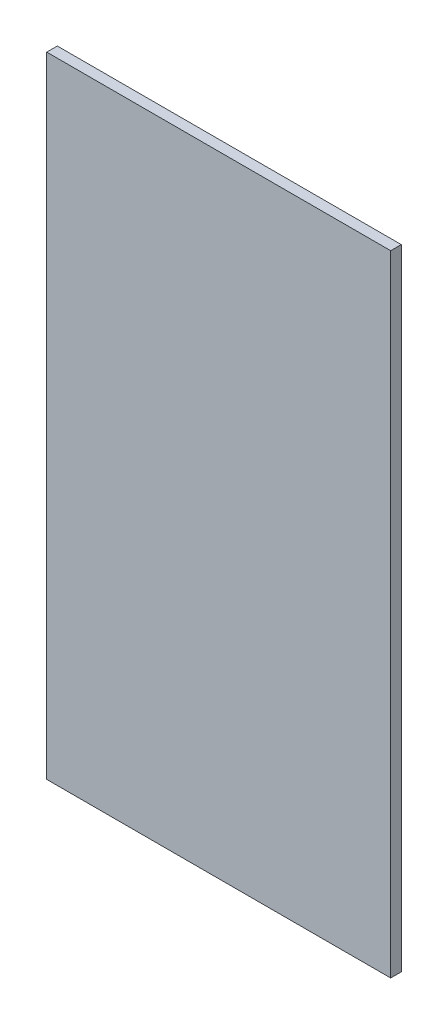
SolidWorks part; units mm, degrees
ref_plane "Plan de face" through (0, 0, 0) normal (0, 0, 1) x (1, 0, 0)
ref_plane "Plan de dessus" through (0, 0, 0) normal (0, 1, 0) x (1, 0, 0)
ref_plane "Plan de droite" through (0, 0, 0) normal (1, 0, 0) x (0, 0, -1)
sketch "Esquisse1" plane through (0, 0, 0) normal (0, 0, 1) x (1, 0, 0)
  line L1 (-82.1418, 217.7685) -> (80.3582, 217.7685)
  line L2 (-82.1418, 217.7685) -> (-82.1418, -79.8315)
  line L3 (-82.1418, -79.8315) -> (80.3582, -79.8315)
  line L4 (80.3582, 217.7685) -> (80.3582, -79.8315)
extrude "Boss.-Extru.2" add sketch "Esquisse1" along normal blind 5 contours L2 L1 L4 L3
sketch3d "Esquisse3D1" [suppressed]
  line L0 (25.4949, 138.1354, 0) -> (24.8506, 141.2765, 0)
  line L1 (24.8506, 141.2765, 0) -> (26.703, 140.5516, 0)
  line L2 (26.703, 140.5516, 0) -> (25.7982, 142.6197, 0)
  line L3 (25.7982, 142.6197, 0) -> (27.3876, 142.404, 0)
  line L4 (33.6186, 143.1405, 0) -> (35.1655, 140.581, 0)
  line L5 (35.1655, 140.581, 0) -> (32.9355, 140.9303, 0)
  line L6 (32.9355, 140.9303, 0) -> (34.252, 139.5332, 0)
  line L7 (34.252, 139.5332, 0) -> (32.64, 138.781, 0)
  line L8 (32.64, 138.781, 0) -> (34.252, 136.8197, 0)
  line L9 (34.252, 136.8197, 0) -> (31.3863, 137.0998, 0)
  line L10 (31.3863, 137.0998, 0) -> (31.3863, 135.0465, 0)
  line L11 (-7.8933, 102.1902, 0) -> (-6.8333, 103.7111, 0)
  line L12 (-6.8333, 103.7111, 0) -> (-4.8975, 102.1902, 0)
  line L13 (44.4221, 93.8184, 0) -> (52.0224, 96.6312, 0)
  line L14 (52.0224, 96.6312, 0) -> (51.3025, 98.5764, 0)
  line L15 (51.3025, 98.5764, 0) -> (44.2109, 95.6765, 0)
  line L16 (47.6223, 90.9727, 0) -> (53.8358, 90.9727, 0)
  line L17 (53.8358, 90.9727, 0) -> (54.506, 89.3336, 0)
  line L18 (54.506, 89.3336, 0) -> (48.2236, 89.0886, 0)
  line L19 (43.8542, 83.717, 0) -> (43.8542, 85.5209, 0)
  line L20 (-40.7515, 93.6509, 0) -> (-50.4113, 95.8339, 0)
  line L21 (-50.4113, 95.8339, 0) -> (-50.7933, 97.5258, 0)
  line L22 (-50.7933, 97.5258, 0) -> (-40.296, 95.1535, 0)
  line L23 (-55.0501, 88.248, 0) -> (-45.1721, 89.5578, 0)
  line L24 (-45.4449, 91.1951, 0) -> (-55.323, 89.8853, 0)
  line L25 (-59.5014, 81.3608, 0) -> (-38.9454, 86.0024, 0)
  line L26 (-38.9454, 86.0024, 0) -> (-39.4037, 88.032, 0)
  line L27 (-39.4037, 88.032, 0) -> (-59.3142, 83.0458, 0)
  line L28 (-59.3142, 83.0458, 0) -> (-59.5014, 81.3608, 0)
  line L29 (-19.8014, 144.3855, 0) -> (-17.5483, 143.5845, 0)
  line L30 (-17.5483, 143.5845, 0) -> (-18.7753, 143.3169, 0)
  line L31 (-18.7753, 143.3169, 0) -> (-16.7171, 142.5851, 0)
  line L32 (-16.7171, 142.5851, 0) -> (-18.7374, 141.44, 0)
  line L33 (-18.7374, 141.44, 0) -> (-18.7374, 140.4351, 0)
  line L34 (-25.2305, 145.307, 0) -> (-27.1997, 143.6168, 0)
  line L35 (-27.1997, 143.6168, 0) -> (-25.2563, 142.8175, 0)
  line L36 (-25.2563, 142.8175, 0) -> (-26.8236, 140.7957, 0)
  line L37 (-26.8236, 140.7957, 0) -> (-25.554, 139.9964, 0)
  line L38 (-25.554, 139.9964, 0) -> (-26.5605, 138.6981, 0)
  line L39 (-26.5605, 138.6981, 0) -> (-24.4569, 139.1657, 0)
  line L40 (-24.4569, 139.1657, 0) -> (-24.5171, 138.2709, 0)
  line L41 (-13.6094, 141.3107, 0) -> (-13.6094, 141.8817, 0)
  line L42 (-13.6094, 141.8817, 0) -> (-14.3403, 142.6127, 0)
  line L43 (-14.3403, 142.6127, 0) -> (-13.4864, 142.6127, 0)
  line L44 (-13.4864, 142.6127, 0) -> (-14.1883, 143.5119, 0)
  line L45 (-14.1883, 143.5119, 0) -> (-14.1172, 144.0887, 0)
  line L46 (-14.1172, 144.0887, 0) -> (-12.8524, 143.7836, 0)
  line L47 (-12.8524, 143.7836, 0) -> (-12.5954, 145.8685, 0)
  line L48 (-12.5954, 145.8685, 0) -> (-11.6249, 144.898, 0)
  line L49 (-11.6249, 144.898, 0) -> (-11.6249, 145.9572, 0)
  line L50 (-11.6249, 145.9572, 0) -> (-10.7216, 145.054, 0)
  line L51 (-10.7216, 145.054, 0) -> (-10.2033, 146.2516, 0)
  line L52 (-10.2033, 146.2516, 0) -> (-9.592, 146.2516, 0)
  line L53 (-9.592, 146.2516, 0) -> (-9.592, 144.8252, 0)
  line L54 (-9.592, 144.8252, 0) -> (-8.3693, 144.8252, 0)
  line L55 (-8.3693, 144.8252, 0) -> (-8.8222, 144.3723, 0)
  line L56 (-8.8222, 144.3723, 0) -> (-8.1316, 143.6817, 0)
  line L57 (-8.1316, 143.6817, 0) -> (-9.0308, 142.786, 0)
  circle A0 centre (20.6935, 109.8595, 0) radius 0.7549
  circle A1 centre (-18.212, 111.9103, 0) radius 1.2299
  spline S0 degree 2 poles (-20.3633, 162.7652, 0) (-12.0724, 165.7872, 0) (-3.3622, 164.1853, 0) knots 0 0 0 1 1 1
  spline S1 degree 2 poles (-81.8789, 154.9416, 0) (-71.547, 187.9168, 0) (-40.4422, 200.8183, 0) knots 0 0 0 1 1 1
  spline S2 degree 2 poles (-30.1118, 204.7729, 0) (-22.0747, 208.713, 0) (-13.1407, 209.3049, 0) knots 0 0 0 1 1 1
  spline S3 degree 2 poles (-30.1118, 204.7729, 0) (-23.7254, 212.8374, 0) (-13.6228, 210.7513, 0) knots 0 0 0 1 1 1
  spline S4 degree 1 poles (-38.3081, 201.6872, 0) (-33.101, 203.905, 0) knots 0 0 1 1
  spline S5 degree 2 poles (-38.3081, 201.6872, 0) (-32.1102, 216.2852, 0) (-16.612, 212.2942, 0) knots 0 0 0 1 1 1
  spline S6 degree 2 poles (-33.101, 203.905, 0) (-27.269, 212.5853, 0) (-16.612, 212.2942, 0) knots 0 0 0 1 1 1
  spline S7 degree 2 poles (-40.4422, 200.8183, 0) (-33.2225, 220.256, 0) (-13.5264, 212.3906, 0) knots 0 0 0 1 1 1
  spline S8 degree 2 poles (-74.1656, 164.0776, 0) (-63.2097, 185.081, 0) (-42.1866, 195.7719, 0) knots 0 0 0 1 1 1
  spline S9 degree 2 poles (-74.1656, 164.0776, 0) (-68.3516, 165.8152, 0) (-62.304, 166.0704, 0) knots 0 0 0 1 1 1
  spline S10 degree 2 poles (-62.304, 166.0704, 0) (-57.137, 181.3077, 0) (-43.0407, 188.655, 0) knots 0 0 0 1 1 1
  spline S11 degree 2 poles (-43.0407, 188.655, 0) (-42.6351, 192.216, 0) (-42.1866, 195.7719, 0) knots 0 0 0 1 1 1
  spline S12 degree 2 poles (-42.1039, 189.1121, 0) (-39.3919, 191.2502, 0) (-36.4025, 192.9733, 0) knots 0 0 0 1 1 1
  spline S13 degree 2 poles (-42.1039, 189.1121, 0) (-41.8681, 192.8762, 0) (-40.4146, 196.3519, 0) knots 0 0 0 1 1 1
  spline S14 degree 2 poles (-40.4146, 196.3519, 0) (-37.3779, 198.6245, 0) (-34.0194, 200.3942, 0) knots 0 0 0 1 1 1
  spline S15 degree 2 poles (-36.4025, 192.9733, 0) (-35.4533, 196.7619, 0) (-34.0194, 200.3942, 0) knots 0 0 0 1 1 1
  spline S16 degree 2 poles (-28.6197, 202.7471, 0) (-30.5389, 199.6184, 0) (-32.2698, 196.3821, 0) knots 0 0 0 1 1 1
  spline S17 degree 2 poles (-32.2698, 196.3821, 0) (-33.9733, 195.2148, 0) (-35.3467, 193.6672, 0) knots 0 0 0 1 1 1
  spline S18 degree 2 poles (-35.3467, 193.6672, 0) (-34.5925, 197.836, 0) (-32.2698, 201.3595, 0) knots 0 0 0 1 1 1
  spline S19 degree 2 poles (-32.2698, 201.3595, 0) (-30.5285, 202.2743, 0) (-28.6197, 202.7471, 0) knots 0 0 0 1 1 1
  spline S20 degree 2 poles (-60.4696, 166.1594, 0) (-54.2515, 166.3089, 0) (-48.1266, 165.2464, 0) knots 0 0 0 1 1 1
  spline S21 degree 2 poles (-60.4696, 166.1594, 0) (-55.4726, 179.4779, 0) (-43.3205, 186.6548, 0) knots 0 0 0 1 1 1
  spline S22 degree 2 poles (-43.3205, 186.6548, 0) (-42.3946, 175.2561, 0) (-48.1266, 165.2464, 0) knots 0 0 0 1 1 1
  spline S23 degree 2 poles (-41.7618, 187.1744, 0) (-41.2309, 175.3441, 0) (-46.8276, 164.8978, 0) knots 0 0 0 1 1 1
  spline S24 degree 2 poles (-46.8276, 164.8978, 0) (-43.247, 163.3476, 0) (-39.4887, 162.3, 0) knots 0 0 0 1 1 1
  spline S25 degree 1 poles (-41.7618, 187.1744, 0) (-36.5661, 191.3959, 0) knots 0 0 1 1
  spline S26 degree 2 poles (-36.5661, 191.3959, 0) (-40.8864, 177.7324, 0) (-37.4753, 163.8587, 0) knots 0 0 0 1 1 1
  spline S27 degree 1 poles (-39.4887, 162.3, 0) (-37.4753, 163.8587, 0) knots 0 0 1 1
  spline S28 degree 2 poles (-76.2798, 159.5792, 0) (-69.992, 162.7295, 0) (-62.9649, 162.8139, 0) knots 0 0 0 1 1 1
  spline S29 degree 2 poles (-76.2798, 159.5792, 0) (-69.9421, 161.1878, 0) (-63.4163, 161.3345, 0) knots 0 0 0 1 1 1
  spline S30 degree 1 poles (-63.4163, 161.3345, 0) (-62.9649, 162.8139, 0) knots 0 0 1 1
  spline S31 degree 2 poles (-61.3909, 162.9674, 0) (-55.0995, 163.4742, 0) (-49.0038, 161.9057, 0) knots 0 0 0 1 1 1
  spline S32 degree 2 poles (-61.7094, 161.5517, 0) (-55.5657, 162.2035, 0) (-49.5347, 160.9147, 0) knots 0 0 0 1 1 1
  spline S33 degree 1 poles (-61.7094, 161.5517, 0) (-61.3909, 162.9674, 0) knots 0 0 1 1
  spline S34 degree 1 poles (-49.5347, 160.9147, 0) (-49.0038, 161.9057, 0) knots 0 0 1 1
  spline S35 degree 2 poles (-48.0169, 161.6806, 0) (-43.5, 161.5556, 0) (-39.4656, 159.5212, 0) knots 0 0 0 1 1 1
  spline S36 degree 1 poles (-48.5064, 160.5577, 0) (-48.0169, 161.6806, 0) knots 0 0 1 1
  spline S37 degree 2 poles (-48.5064, 160.5577, 0) (-43.7468, 159.7781, 0) (-39.3793, 157.7361, 0) knots 0 0 0 1 1 1
  spline S38 degree 2 poles (-39.4656, 159.5212, 0) (-22.4346, 170.5781, 0) (-2.079, 169.8481, 0) knots 0 0 0 1 1 1
  spline S39 degree 2 poles (-39.3793, 157.7361, 0) (-22.481, 169.1841, 0) (-2.1495, 167.9444, 0) knots 0 0 0 1 1 1
  spline S40 degree 2 poles (-2.079, 169.8481, 0) (7.837, 174.0448, 0) (18.3102, 176.5544, 0) knots 0 0 0 1 1 1
  spline S41 degree 2 poles (-2.1495, 167.9444, 0) (7.3531, 172.8749, 0) (17.9103, 174.612, 0) knots 0 0 0 1 1 1
  spline S42 degree 1 poles (17.9103, 174.612, 0) (18.3102, 176.5544, 0) knots 0 0 1 1
  spline S43 degree 2 poles (19.429, 174.7579, 0) (30.2167, 177.6524, 0) (40.0743, 172.5823, 0) knots 0 0 0 1 1 1
  spline S44 degree 1 poles (19.429, 174.7579, 0) (19.5216, 176.6095, 0) knots 0 0 1 1
  spline S45 degree 2 poles (19.5216, 176.6095, 0) (24.9252, 177.4093, 0) (30.3534, 176.8409, 0) knots 0 0 0 1 1 1
  spline S46 degree 2 poles (34.8635, 176.1715, 0) (36.5707, 175.4775, 0) (38.3125, 174.8754, 0) knots 0 0 0 1 1 1
  spline S47 degree 2 poles (40.0743, 172.5823, 0) (54.0193, 182.7239, 0) (71.236, 182.351, 0) knots 0 0 0 1 1 1
  spline S48 degree 3 poles (38.3125, 174.8754, 0) (49.367, 179.5773, 0) (58.4974, 187.4411, 0) (71.236, 182.351, 0) knots 0 0 0 0 1 1 1 1
  spline S49 degree 2 poles (-0.3107, 166.5454, 5) (8.2133, 168.9997, 5) (17.0379, 169.8968, 5) knots 0 0 0 1 1 1
  spline S50 degree 2 poles (18.2651, 169.4734, 0) (28.9991, 169.6026, 0) (39.2311, 166.3451, 0) knots 0 0 0 1 1 1
  spline S51 degree 2 poles (-0.3107, 166.5454, 5) (0.2947, 156.6212, 5) (2.3737, 146.8992, 5) knots 0 0 0 1 1 1
  spline S52 degree 2 poles (-3.3622, 164.1853, 0) (-1.3802, 155.3146, 0) (-1.0378, 146.2353, 0) knots 0 0 0 1 1 1
  spline S53 degree 2 poles (2.3737, 146.8992, 5) (5.1648, 147.1501, 5) (7.9657, 147.0707, 5) knots 0 0 0 1 1 1
  spline S54 degree 2 poles (7.9657, 147.0707, 5) (5.7987, 145.3956, 5) (3.5567, 143.822, 5) knots 0 0 0 1 1 1
  spline S55 degree 2 poles (-26.4609, 203.3989, 0) (-29.8737, 196.9084, 0) (-35.432, 192.118, 0) knots 0 0 0 1 1 1
  spline S56 degree 3 poles (-35.432, 192.118, 0) (-37.2126, 186.143, 0) (-37.7046, 177.1886, 0) (-37.8705, 168.5072, 0) (-35.9602, 164.8776, 0) knots 0 0 0 0 0.597354 1 1 1 1
  spline S57 degree 2 poles (-26.4609, 203.3989, 0) (-18.3206, 205.6479, 0) (-9.9003, 206.3588, 0) knots 0 0 0 1 1 1
  spline S58 degree 2 poles (-6.9753, 185.3091, 0) (-5.6223, 196.2378, 0) (-9.9003, 206.3588, 0) knots 0 0 0 1 1 1
  spline S59 degree 2 poles (-5.6694, 185.9881, 0) (-2.2964, 196.9777, 0) (-8.3855, 206.62, 0) knots 0 0 0 1 1 1
  spline S60 degree 2 poles (-8.3855, 206.62, 0) (-2.3112, 207.5622, 0) (3.8369, 207.508, 0) knots 0 0 0 1 1 1
  spline S61 degree 2 poles (-5.6694, 185.9881, 0) (-0.7771, 188.0567, 0) (4.307, 189.5921, 0) knots 0 0 0 1 1 1
  spline S62 degree 2 poles (3.8369, 207.508, 0) (3.1718, 198.5253, 0) (4.307, 189.5921, 0) knots 0 0 0 1 1 1
  spline S63 degree 2 poles (5.3216, 190.0513, 0) (16.4175, 194.2656, 0) (24.3421, 203.1003, 0) knots 0 0 0 1 1 1
  spline S64 degree 2 poles (5.3216, 190.0513, 0) (4.0876, 198.7199, 0) (4.8055, 207.4499, 0) knots 0 0 0 1 1 1
  spline S65 degree 2 poles (4.8055, 207.4499, 0) (14.9501, 206.9868, 0) (24.3421, 203.1003, 0) knots 0 0 0 1 1 1
  spline S66 degree 2 poles (-13.5264, 212.3906, 0) (-12.8637, 213.8075, 0) (-11.7744, 214.9114, 0) knots 0 0 0 1 1 1
  spline S67 degree 2 poles (-11.7744, 214.9114, 0) (-11.8968, 216.2353, 0) (-12.829, 217.1908, 0) knots 0 0 0 1 1 1
  spline S68 degree 2 poles (-12.829, 217.1908, 0) (-12.397, 217.5679, 0) (-11.8278, 217.5417, 0) knots 0 0 0 1 1 1
  spline S69 degree 2 poles (-11.8278, 217.5417, 0) (-11.4021, 216.4098, 0) (-10.8601, 215.3284, 0) knots 0 0 0 1 1 1
  spline S70 degree 2 poles (-10.8601, 215.3284, 0) (-9.6033, 215.1745, 0) (-8.4338, 215.6233, 0) knots 0 0 0 1 1 1
  spline S71 degree 2 poles (-8.4338, 215.6233, 0) (-6.9374, 213.4569, 0) (-8.054, 211.0468, 0) knots 0 0 0 1 1 1
  spline S72 degree 1 poles (-8.054, 211.0468, 0) (-6.9336, 211.0468, 0) knots 0 0 1 1
  spline S73 degree 2 poles (-6.9336, 211.0468, 0) (-6.4376, 213.3987, 0) (-4.5599, 214.8068, 0) knots 0 0 0 1 1 1
  spline S74 degree 1 poles (-4.5599, 214.8068, 0) (-3.6674, 214.8068, 0) knots 0 0 1 1
  spline S75 degree 2 poles (-3.6674, 214.8068, 0) (-2.5044, 215.4736, 0) (-1.7304, 216.5728, 0) knots 0 0 0 1 1 1
  spline S76 degree 1 poles (-1.7304, 216.5728, 0) (-0.7619, 215.7752, 0) knots 0 0 1 1
  spline S77 degree 2 poles (-0.7619, 215.7752, 0) (-1.8056, 215.0951, 0) (-2.8318, 214.389, 0) knots 0 0 0 1 1 1
  spline S78 degree 2 poles (-2.8318, 214.389, 0) (-2.304, 213.5052, 0) (-2.2621, 212.471, 0) knots 0 0 0 1 1 1
  spline S79 degree 3 poles (-2.2621, 212.471, 0) (-0.8127, 215.1566, 0) (4.5483, 215.9031, 0) (4.7186, 211.3255, 0) knots 0 0 0 0 1 1 1 1
  spline S80 degree 1 poles (-1.2795, 211.1904, 0) (3.4488, 211.1634, 0) knots 0 0 1 1
  spline S81 degree 2 poles (-1.2795, 211.1904, 0) (-0.8983, 213.4433, 0) (1.4494, 213.487, 0) knots 0 0 0 1 1 1
  spline S82 degree 1 poles (3.4488, 211.1634, 0) (3.4488, 211.8929, 0) knots 0 0 1 1
  spline S83 degree 2 poles (3.4488, 211.8929, 0) (2.6866, 212.721, 0) (1.5575, 212.8926, 0) knots 0 0 0 1 1 1
  spline S84 degree 1 poles (1.5575, 212.8926, 0) (1.4494, 213.487, 0) knots 0 0 1 1
  spline S85 degree 2 poles (4.7186, 211.3255, 0) (10.3448, 210.842, 0) (15.8791, 209.7244, 0) knots 0 0 0 1 1 1
  spline S86 degree 3 poles (15.8791, 209.7244, 0) (25.0713, 214.7973, 0) (32.7248, 215.4471, 0) (37.3752, 204.8654, 0) knots 0 0 0 0 1 1 1 1
  spline S87 degree 2 poles (18.5993, 209.2881, 0) (27.1258, 207.7311, 0) (35.403, 205.1641, 0) knots 0 0 0 1 1 1
  spline S88 degree 2 poles (18.5993, 209.2881, 0) (29.2578, 216.5573, 0) (35.403, 205.1641, 0) knots 0 0 0 1 1 1
  spline S89 degree 2 poles (30.7317, 202.5764, 0) (39.609, 193.2632, 0) (40.7346, 180.3478, 0) knots 0 0 0 1 1 1
  spline S90 degree 2 poles (30.7317, 202.5764, 0) (43.615, 195.0713, 0) (40.7346, 180.3478, 0) knots 0 0 0 1 1 1
  spline S91 degree 2 poles (37.3752, 204.8654, 0) (61.4632, 197.8726, 0) (80.1441, 181.1197, 0) knots 0 0 0 1 1 1
  spline S92 degree 2 poles (80.1441, 181.1197, 0) (71.9955, 179.743, 0) (64.2587, 176.8256, 0) knots 0 0 0 1 1 1
  spline S93 degree 2 poles (-20.3633, 162.7652, 0) (-18.4917, 155.1787, 0) (-17.5626, 147.4248, 0) knots 0 0 0 1 1 1
  spline S94 degree 3 poles (-25.3765, 160.8618, 0) (-25.8876, 157.4446, 0) (-29.3098, 150.9494, 0) (-27.497, 146.32, 0) (-25.2305, 145.307, 0) knots 0 0 0 0 0.669542 1 1 1 1
  spline S95 degree 2 poles (-13.6558, 181.193, 0) (-20.0535, 177.8034, 0) (-25.3006, 172.8088, 0) knots 0 0 0 1 1 1
  spline S96 degree 3 poles (39.2311, 166.3451, 0) (37.3085, 163.6675, 0) (35.5849, 160.7515, 0) (31.7572, 155.5609, 0) (29.6845, 153.1021, 0) (28.466, 150.3725, 0) (30.219, 147.5099, 0) (29.9717, 146.1817, 0) (29.0598, 144.7175, 0) knots 0 0 0 0 0.365812 0.436766 0.679225 0.725166 0.865872 1 1 1 1
  spline S97 degree 2 poles (17.0379, 169.8968, 5) (17.8049, 159.8318, 5) (15.2967, 150.0591, 5) knots 0 0 0 1 1 1
  spline S98 degree 2 poles (18.2651, 169.4734, 0) (18.642, 159.407, 0) (16.0406, 149.6871, 0) knots 0 0 0 1 1 1
  spline S99 degree 2 poles (25.4949, 138.1354, 0) (19.8938, 140.938, 0) (13.8167, 142.4443, 0) knots 0 0 0 1 1 1
  spline S100 degree 1 poles (29.0598, 144.7175, 0) (25.8573, 145.2632, 0) knots 0 0 1 1
  spline S101 degree 1 poles (25.8573, 145.2632, 0) (27.3876, 142.404, 0) knots 0 0 1 1
  spline S102 degree 2 poles (62.7677, 176.1123, 0) (51.1108, 172.8074, 0) (41.2557, 165.7526, 0) knots 0 0 0 1 1 1
  spline S103 degree 2 poles (-25.3765, 160.8618, 0) (-34.8575, 158.6597, 0) (-41.7887, 151.8381, 0) knots 0 0 0 1 1 1
  spline S104 degree 2 poles (-41.7887, 151.8381, 0) (-45.5723, 154.0646, 0) (-49.6475, 155.694, 0) knots 0 0 0 1 1 1
  spline S105 degree 3 poles (-49.6475, 155.694, 0) (-50.3292, 152.7209, 0) (-51.263, 147.5915, 0) (-48.4379, 141.0974, 0) (-49.9537, 137.6286, 0) knots 0 0 0 0 0.406946 1 1 1 1
  spline S106 degree 3 poles (-49.9537, 137.6286, 0) (-49.4637, 141.7607, 0) (-51.9256, 146.6221, 0) (-51.0045, 152.9563, 0) (-50.3667, 156.0071, 0) knots 0 0 0 0 0.604226 1 1 1 1
  spline S107 degree 2 poles (-50.3667, 156.0071, 0) (-55.8567, 159.1908, 0) (-62.2451, 158.7047, 0) knots 0 0 0 1 1 1
  spline S108 degree 2 poles (-81.8789, 154.9416, 0) (-73.1076, 158.718, 0) (-63.52, 158.8017, 0) knots 0 0 0 1 1 1
  spline S109 degree 1 poles (-35.9602, 164.8776, 0) (-34.1549, 166.0675, 0) knots 0 0 1 1
  spline S110 degree 1 poles (19.475, 178.4365, 0) (20.6201, 178.551, 0) knots 0 0 1 1
  spline S111 degree 2 poles (19.475, 178.4365, 0) (20.2478, 181.8847, 0) (21.9943, 184.9637, 0) knots 0 0 0 1 1 1
  spline S112 degree 2 poles (21.9943, 184.9637, 0) (26.4105, 183.1694, 0) (31.0408, 182.0436, 0) knots 0 0 0 1 1 1
  spline S113 degree 2 poles (20.6201, 178.551, 0) (21.2694, 181.1962, 0) (22.4523, 183.6468, 0) knots 0 0 0 1 1 1
  spline S114 degree 2 poles (22.4523, 183.6468, 0) (26.4698, 182.231, 0) (30.64, 181.3566, 0) knots 0 0 0 1 1 1
  spline S115 degree 2 poles (30.64, 181.3566, 0) (29.3154, 179.2318, 0) (30.3534, 176.8409, 0) knots 0 0 0 1 1 1
  spline S116 degree 2 poles (34.8635, 176.1715, 0) (38.8155, 180.8189, 0) (35.1633, 186.2234, 0) knots 0 0 0 1 1 1
  spline S117 degree 3 poles (35.1633, 186.2234, 0) (35.1476, 187.6953, 0) (36.0987, 188.4985, 0) (35.5256, 190.99, 0) (34.6866, 189.8918, 0) (33.7377, 188.8613, 0) (33.8414, 189.7547, 0) (33.6335, 190.8073, 0) (32.2189, 188.5315, 0) (32.4198, 188.4214, 0) (32.2326, 187.2048, 0) knots 0 0 0 0 0.320929 0.395136 0.507176 0.587018 0.637415 0.685791 0.823461 1 1 1 1
  spline S118 degree 3 poles (32.2326, 187.2048, 0) (30.8782, 186.2445, 0) (31.1102, 184.8075, 0) (31.2817, 183.0501, 0) knots 0 0 0 0 1 1 1 1
  spline S119 degree 2 poles (31.0408, 182.0436, 0) (31.7295, 182.4022, 0) (31.2817, 183.0501, 0) knots 0 0 0 1 1 1
  spline S120 degree 1 poles (5.9368, 188.1717, 0) (4.902, 188.1717, 0) knots 0 0 1 1
  spline S121 degree 1 poles (5.9368, 188.1717, 0) (6.2067, 182.0528, 0) knots 0 0 1 1
  spline S122 degree 3 poles (6.2067, 182.0528, 0) (6.4988, 179.6696, 0) (2.862, 182.1853, 0) (5.528, 182.2136, 0) knots 0 0 0 0 1 1 1 1
  spline S123 degree 2 poles (5.528, 182.2136, 0) (5.2442, 185.1957, 0) (4.902, 188.1717, 0) knots 0 0 0 1 1 1
  spline S124 degree 2 poles (-6.9753, 185.3091, 0) (-9.0858, 185.1419, 0) (-10.5506, 183.54, 0) knots 0 0 0 1 1 1
  spline S125 degree 3 poles (70.8623, 156.6044, 0) (69.063, 152.3437, 0) (63.9156, 156.0474, 0) (60.9405, 161.9698, 0) (65.0025, 167.9753, 0) (65.1782, 173.0968, 0) (64.2587, 176.8256, 0) knots 0 0 0 0 0.306674 0.494435 0.612771 1 1 1 1
  spline S126 degree 3 poles (62.7677, 176.1123, 0) (65.9981, 171.2593, 0) (58.605, 165.0163, 0) (62.5269, 156.512, 0) (66.9671, 152.15, 0) (71.76, 153.6937, 0) (70.8623, 156.6044, 0) knots 0 0 0 0 0.449633 0.649006 0.814462 1 1 1 1
  spline S127 degree 3 poles (41.2557, 165.7526, 0) (41.1999, 162.5912, 0) (39.843, 156.3381, 0) (39.8469, 146.3629, 0) (36.9237, 144.938, 0) (33.6186, 143.1405, 0) knots 0 0 0 0 0.420838 0.74092 1 1 1 1
  spline S128 degree 2 poles (8.3795, 102.547, 0) (10.8006, 101.9446, 0) (12.8664, 103.2812, 0) knots 0 0 0 1 1 1
  spline S129 degree 2 poles (12.8664, 103.2812, 0) (10.7862, 105.6316, 0) (7.6452, 106.1366, 0) knots 0 0 0 1 1 1
  spline S130 degree 1 poles (8.3795, 102.547, 0) (7.6452, 106.1366, 0) knots 0 0 1 1
  spline S131 degree 1 poles (4.8715, 102.6286, 0) (4.6267, 106.2997, 0) knots 0 0 1 1
  spline S132 degree 2 poles (-11.8109, 103.0659, 0) (-4.0766, 107.0254, 0) (4.6267, 106.2997, 0) knots 0 0 0 1 1 1
  spline S133 degree 2 poles (4.8715, 102.6286, 0) (0, 102.1302, 0) (-4.8975, 102.1902, 0) knots 0 0 0 1 1 1
  spline S134 degree 2 poles (-11.8109, 103.0659, 0) (-9.923, 102.2977, 0) (-7.8933, 102.1902, 0) knots 0 0 0 1 1 1
  spline S135 degree 3 poles (18.1536, 109.0885, 0) (15.5218, 113.2757, 0) (19.4012, 122.4912, 0) (29.8529, 121.5289, 0) (35.6076, 116.1517, 0) (33.6365, 107.1366, 0) (27.378, 104.031, 0) (23.7324, 106.0496, 0) knots 0 0 0 0 0.300583 0.467166 0.615819 0.760416 1 1 1 1
  spline S136 degree 3 poles (18.1536, 109.0885, 0) (18.4637, 110.1015, 0) (19.9305, 112.7255, 0) (24.3263, 113.991, 0) (26.2739, 109.1371, 0) (24.7175, 107.681, 0) (23.7324, 106.0496, 0) knots 0 0 0 0 0.267348 0.487066 0.732963 1 1 1 1
  spline S137 degree 3 poles (-19.4597, 109.3063, 0) (-22.4698, 106.7722, 0) (-29.3413, 108.8458, 0) (-30.9234, 117.46, 0) (-26.2258, 122.3441, 0) (-19.9207, 123.4067, 0) (-13.5297, 119.5358, 0) (-12.3686, 113.5309, 0) (-15.0112, 111.3678, 0) knots 0 0 0 0 0.238197 0.385038 0.519406 0.660915 0.794208 1 1 1 1
  spline S138 degree 3 poles (-19.4597, 109.3063, 0) (-20.5208, 110.5254, 0) (-21.779, 113.8575, 0) (-18.528, 116.2494, 0) (-15.3317, 114.9332, 0) (-15.1761, 112.5074, 0) (-15.0112, 111.3678, 0) knots 0 0 0 0 0.383435 0.55282 0.738726 1 1 1 1
  spline S139 degree 3 poles (1.2886, 89.4652, 0) (3.0208, 91.9814, 0) (-0.6159, 92.6707, 0) (-5.1504, 91.2525, 0) (-0.9742, 89.4078, 0) (1.2886, 89.4652, 0) (3.0208, 91.9814, 0) (-0.6159, 92.6707, 0) knots -0.53175 -0.296822 -0.131141 0 0.208608 0.46825 0.703178 0.868859 1 1.208608 1.46825 1.703178 only from (2.2747, 91.402, 0) to (2.2747, 91.402, 0)
  spline S140 degree 3 poles (44.2109, 95.6765, 0) (42.7416, 95.4682, 0) (42.6795, 93.6232, 0) (44.4221, 93.8184, 0) knots 0 0 0 0 1 1 1 1
  spline S141 degree 2 poles (47.6223, 90.9727, 0) (47.414, 89.8713, 0) (48.2236, 89.0886, 0) knots 0 0 0 1 1 1
  spline S142 degree 3 poles (43.8542, 85.5209, 0) (46.5859, 85.3334, 0) (50.1963, 84.4134, 0) (54.1394, 83.5768, 0) (57.0372, 82.4066, 0) (57.6992, 81.5319, 0) (56.8251, 80.9015, 0) (54.2062, 81.7351, 0) (50.0882, 82.4207, 0) (46.5302, 83.0624, 0) (43.8542, 83.717, 0) knots 0 0 0 0 0.245834 0.465431 0.494309 0.534612 0.567201 0.591234 0.774938 1 1 1 1
  spline S143 degree 2 poles (-39.9874, 95.1245, 0) (-38.2228, 93.4829, 0) (-40.7515, 93.6509, 0) knots 0 0 0 1 1 1
  spline S144 degree 2 poles (-45.4449, 91.1951, 0) (-42.9592, 90.7986, 0) (-45.1721, 89.5578, 0) knots 0 0 0 1 1 1
  spline S145 degree 2 poles (-55.323, 89.8853, 0) (-57.9654, 88.7045, 0) (-55.0501, 88.248, 0) knots 0 0 0 1 1 1
  spline S146 degree 3 poles (-63.52, 158.8017, 0) (-63.7995, 151.7866, 0) (-62.9562, 138.0028, 0) (-67.4872, 117.6803, 0) (-72.4057, 104.9931, 0) (-72.6209, 97.932, 0) knots 0 0 0 0 0.340812 0.664704 1 1 1 1
  spline S147 degree 2 poles (-72.6209, 97.932, 0) (-77.0718, 97.7381, 0) (-81.0218, 95.5598, 0) knots 0 0 0 1 1 1
  spline S148 degree 1 poles (-81.0218, 95.5598, 0) (-72.6084, 96.3466, 0) knots 0 0 1 1
  spline S149 degree 2 poles (-55.0552, 97.9809, 0) (-63.1631, 98.798, 0) (-71.2768, 98.0414, 0) knots 0 0 0 1 1 1
  spline S150 degree 3 poles (-71.2768, 98.0414, 0) (-70.2354, 108.3569, 0) (-65.1175, 121.8591, 0) (-61.808, 142.1797, 0) (-62.6512, 152.6235, 0) (-62.2451, 158.7047, 0) knots 0 0 0 0 0.501042 0.697538 1 1 1 1
  spline S151 degree 2 poles (-72.6084, 96.3466, 0) (-72.7602, 91.7089, 0) (-72.2201, 87.0965, 0) knots 0 0 0 1 1 1
  spline S152 degree 2 poles (-72.2201, 87.0965, 0) (-77.4837, 86.4036, 0) (-81.4203, 82.7901, 0) knots 0 0 0 1 1 1
  spline S153 degree 2 poles (-81.4203, 82.7901, 0) (-76.8606, 84.2102, 0) (-72.2201, 85.3348, 0) knots 0 0 0 1 1 1
  spline S154 degree 2 poles (-70.8499, 96.3946, 0) (-71.8232, 91.876, 0) (-71.2414, 87.2923, 0) knots 0 0 0 1 1 1
  spline S155 degree 2 poles (-71.2414, 87.2923, 0) (-64.5107, 88.2639, 0) (-58.0283, 90.3264, 0) knots 0 0 0 1 1 1
  spline S156 degree 1 poles (-58.0283, 90.3264, 0) (-54.0154, 96.101, 0) knots 0 0 1 1
  spline S157 degree 2 poles (-70.8499, 96.3946, 0) (-63.8015, 96.9837, 0) (-56.7559, 96.3946, 0) knots 0 0 0 1 1 1
  spline S158 degree 3 poles (-56.7559, 96.3946, 0) (-58.2756, 93.1217, 0) (-55.2194, 96.5074, 0) (-54.0154, 96.101, 0) knots 0 0 0 0 1 1 1 1
  spline S159 degree 2 poles (-55.0552, 97.9809, 0) (-52.4365, 101.5625, 0) (-50.331, 105.4693, 0) knots 0 0 0 1 1 1
  spline S160 degree 1 poles (-50.331, 105.4693, 0) (-53.03, 104.4977, 0) knots 0 0 1 1
  spline S161 degree 2 poles (-53.03, 104.4977, 0) (-49.9434, 112.0304, 0) (-45.0649, 118.5484, 0) knots 0 0 0 1 1 1
  spline S162 degree 2 poles (-45.0649, 118.5484, 0) (-45.684, 118.5328, 0) (-45.9578, 119.1058, 0) knots 0 0 0 1 1 1
  spline S163 degree 2 poles (-45.9578, 119.1058, 0) (-43.9332, 121.1337, 0) (-41.9942, 123.2437, 0) knots 0 0 0 1 1 1
  spline S164 degree 1 poles (-41.9942, 123.2437, 0) (-44.269, 122.2787, 0) knots 0 0 1 1
  spline S165 degree 2 poles (-44.269, 122.2787, 0) (-42.8881, 124.1317, 0) (-41.684, 126.1044, 0) knots 0 0 0 1 1 1
  spline S166 degree 2 poles (-41.684, 126.1044, 0) (-42.8652, 125.3265, 0) (-44.3034, 125.4495, 0) knots 0 0 0 1 1 1
  spline S167 degree 2 poles (-44.3034, 125.4495, 0) (-35.9061, 134.1781, 0) (-24.5171, 138.2709, 0) knots 0 0 0 1 1 1
  spline S168 degree 2 poles (-17.5626, 147.4248, 0) (-18.5225, 145.7888, 0) (-19.8014, 144.3855, 0) knots 0 0 0 1 1 1
  spline S169 degree 2 poles (-18.7374, 140.4351, 0) (-16.2141, 141.1065, 0) (-13.6094, 141.3107, 0) knots 0 0 0 1 1 1
  spline S170 degree 2 poles (-9.0308, 142.786, 0) (-3.7331, 141.5279, 0) (-1.0378, 146.2353, 0) knots 0 0 0 1 1 1
  spline S171 degree 2 poles (-76.3586, 76.4152, 5) (-74.007, 78.9964, 5) (-70.5868, 79.4893, 5) knots 0 0 0 1 1 1
  spline S172 degree 2 poles (-72.2201, 85.3348, 0) (-69.942, 80.7026, -1.2503) (-70.5868, 79.4893, 5) knots 0 0 0 1 1 1
  spline S173 degree 2 poles (-76.3586, 76.4152, 5) (-73.1145, 76.5117, 5) (-70.085, 77.67, 5) knots 0 0 0 1 1 1
  spline S174 degree 1 poles (-70.085, 77.67, 5) (-67.1363, 71.3963, 5) knots 0 0 1 1
  spline S175 degree 1 poles (-68.9557, 78.2346, 0) (-66.5717, 72.5256, 0) knots 0 0 1 1
  spline S176 degree 2 poles (-66.5717, 72.5256, 0) (-66.2745, 76.6015, 0) (-63.6858, 79.7403, 0) knots 0 0 0 1 1 1
  spline S177 degree 1 poles (-68.9557, 78.2346, 0) (-63.6858, 79.7403, 0) knots 0 0 1 1
  spline S178 degree 2 poles (-70.5868, 85.3866, 0) (-65.6199, 86.7709, 0) (-60.4862, 87.2687, 0) knots 0 0 0 1 1 1
  spline S179 degree 2 poles (-70.5868, 85.3866, 0) (-70.3164, 82.5557, 0) (-69.3949, 79.8658, 0) knots 0 0 0 1 1 1
  spline S180 degree 1 poles (-69.3949, 79.8658, 0) (-61.9292, 82.7516, 0) knots 0 0 1 1
  spline S181 degree 2 poles (-61.9292, 82.7516, 0) (-58.9826, 85.6491, 0) (-63.3483, 84.4005, 0) knots 0 0 0 1 1 1
  spline S182 degree 1 poles (-63.3483, 84.4005, 0) (-60.4862, 87.2687, 0) knots 0 0 1 1
  spline S183 degree 2 poles (31.3863, 135.0465, 0) (44.1571, 128.8042, 0) (49.3242, 115.3723, 0) knots 0 0 0 1 1 1
  spline S184 degree 1 poles (49.3242, 115.3723, 0) (47.1265, 115.8851, 0) knots 0 0 1 1
  spline S185 degree 2 poles (47.1265, 115.8851, 0) (50.579, 107.6182, 0) (53.5494, 99.1659, 0) knots 0 0 0 1 1 1
  spline S186 degree 2 poles (53.5494, 99.1659, 0) (64.257, 104.1746, 0) (76.1362, 102.9801, 0) knots 0 0 0 1 1 1
  spline S187 degree 2 poles (76.1362, 102.9801, 0) (64.4346, 102.2744, 0) (54.2646, 96.4841, 0) knots 0 0 0 1 1 1
  point P292 (20.6935, 109.8595, 0.7549)
  point P305 (-18.212, 111.9103, 1.2299)
